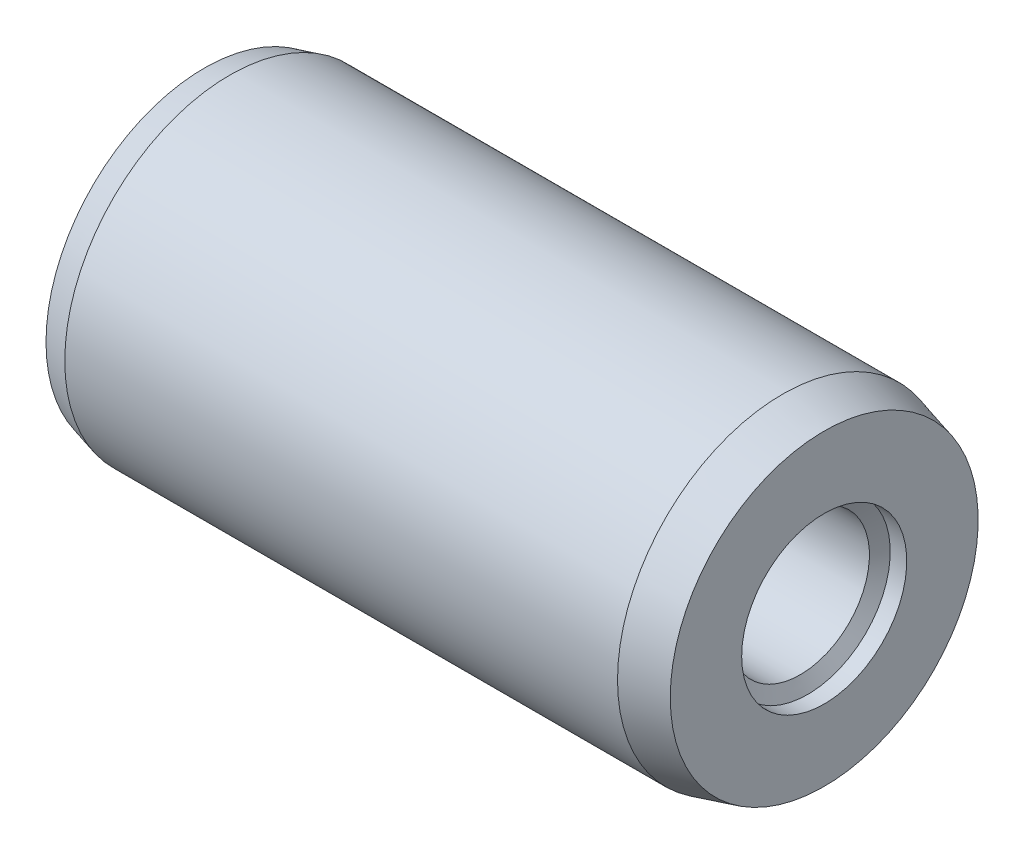
SolidWorks part; units mm, degrees
revolve "Base-Revolve" add sketch "Sketch1" angle 360 about L0
sketch "Sketch1" plane through (0, 0, 0) normal (0, 0, 1) x (1, 0, 0)
  line L0 (-10, 0) -> (106, 0) construction
  line L1 (0, 0) -> (0, 22.3205)
  line L2 (10, 25) -> (93.7, 25)
  line L3 (100, 23.3119) -> (100, 12.5)
  line L4 (43.691, 0) -> (0, 0)
  line L5 (10, 25) -> (0, 22.3205)
  line L6 (100, 23.3119) -> (93.7, 25)
  line L7 (43.691, 0) -> (50, 10.5)
  line L8 (50, 10.5) -> (96.3453, 10.5)
  line L9 (96.3453, 10.5) -> (97.5, 12.5)
  line L10 (96.3453, -10.5) -> (97.5, -12.5) construction
  line L11 (97.5, 12.5) -> (100, 12.5)
  line L12 (43.691, 0) -> (50, -10.5) construction
  dimension "D1" = 15
  dimension "Length" = 100
  dimension "D2" = 75
  dimension "ChamferLengthA" = 6.3
  dimension "D3" = 120
  dimension "Diameter" = 50
  dimension "CboreDia" = 25
  dimension "D4" = 118
  dimension "CboreDepth" = 2.5
  dimension "TapDrillDepth" = 50
  dimension "TapDrillDia" = 21
  dimension "ChamferLengthC" = 10
cosmetic thread "Cosmetic Thread1" [suppressed] parameters "ThreadDepth"=36, "ThreadDia"=24
ref_plane "Plane1" through (0, 0, 0) normal (0, 0, 1) x (1, 0, 0)
ref_plane "Plane2" through (0, 0, 0) normal (0, 1, 0) x (1, 0, 0)
ref_plane "Plane3" through (0, 0, 0) normal (1, 0, 0) x (0, 0, -1)
sketch "Sketch2" plane through (0, 0, 0) normal (0, 0, 1) x (1, 0, 0)
  line L0 (0, 0) -> (26, 0) construction
  line L1 (-10, 0) -> (106, 0) construction
  line L2 (0, 22.3205) -> (0, -22.3205) construction
  line L3 (6.114, 23.9588) -> (6.114, 30)
  line L5 (6.114, 30) -> (-5, 30)
  line L6 (-5, 30) -> (-5, 0)
  line L7 (-5, 0) -> (0, 0)
  line L8 (10, 25) -> (0, 22.3205) construction
  line L9 (93.7, 25) -> (10, 25) construction
  arc A0 (6.114, 23.9588) -> (0, 0) centre (50, 0) ccw
  dimension "D1" = 50
  dimension "D2" = 5
  dimension "D3" = 5
revolve "TypeA" cut sketch "Sketch2" angle 360 about L0
equation "\"D1@Sketch2\" = \"Diameter@Sketch1\""
